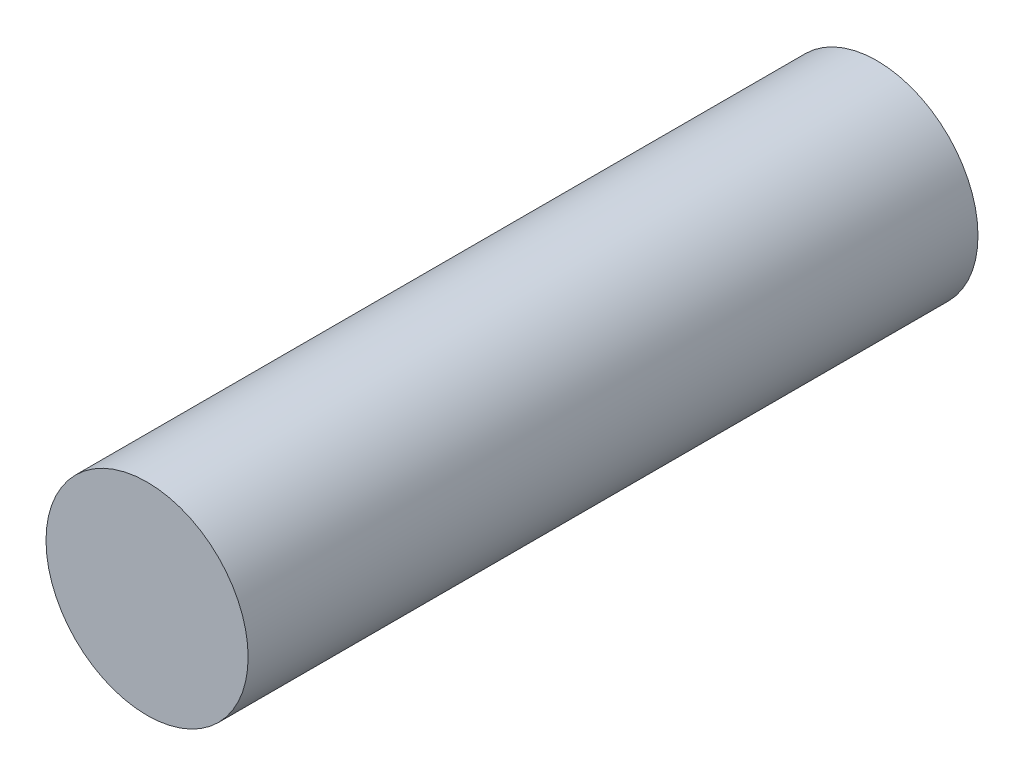
SolidWorks part; units mm, degrees
material "cell_18650_equivalent"
ref_plane "Front Plane" through (0, 0, 0) normal (0, 0, 1) x (1, 0, 0)
ref_plane "Top Plane" through (0, 0, 0) normal (0, 1, 0) x (1, 0, 0)
ref_plane "Right Plane" through (0, 0, 0) normal (1, 0, 0) x (0, 0, -1)
sketch "Sketch3" plane through (0, 0, 0) normal (0, 0, 1) x (1, 0, 0)
  circle A0 centre (-43.2267, 0) radius 9
sketch "Sketch4" plane through (0, 0, 0) normal (0, 0, 1) x (1, 0, 0)
  circle A0 centre (-43.2267, 0) radius 3
extrude "Boss-Extrude4" add sketch "Sketch3" along normal blind 65 contours A0
extrude "Boss-Extrude5" add sketch "Sketch4" against normal blind 1.5 contours A0
